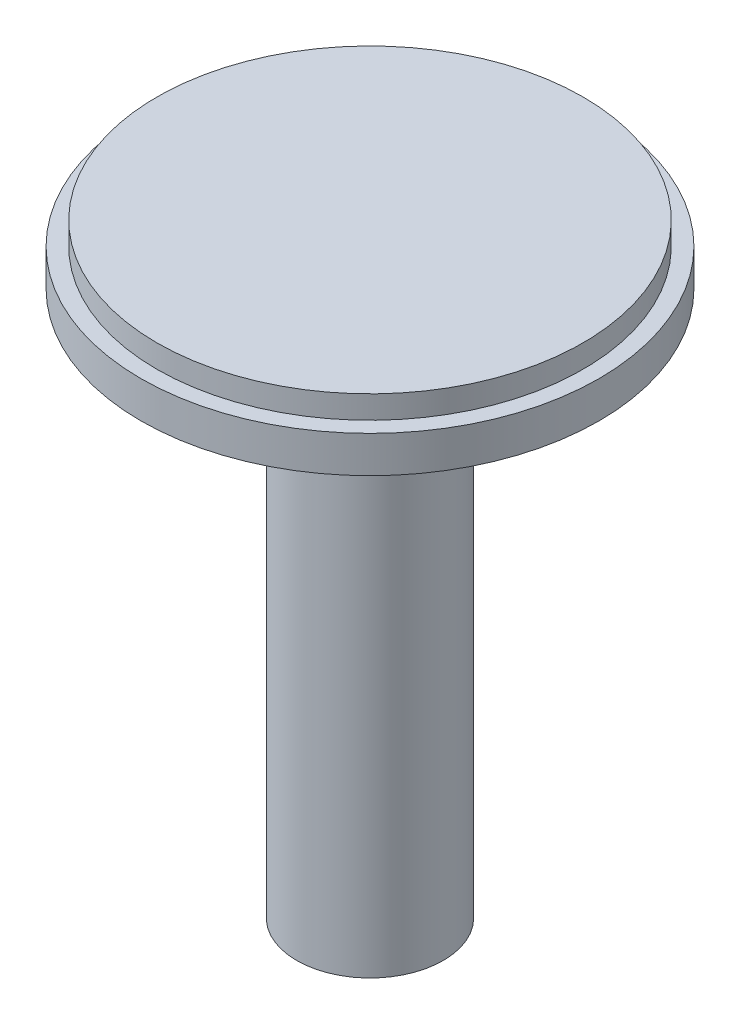
SolidWorks part; units mm, degrees
ref_plane "Front Plane" through (0, 0, 0) normal (0, 0, 1) x (1, 0, 0)
ref_plane "Top Plane" through (0, 0, 0) normal (0, 1, 0) x (1, 0, 0)
ref_plane "Right Plane" through (0, 0, 0) normal (1, 0, 0) x (0, 0, -1)
sketch "Sketch1" plane through (0, 0, 0) normal (0, 1, 0) x (1, 0, 0)
  circle A0 centre (0, 0) radius 16
extrude "Boss-Extrude1" add sketch "Sketch1" along normal blind 119
sketch "Sketch2" plane through (0, 119, 0) normal (0, 1, 0) x (1, 0, 0)
  circle A0 centre (0, 0) radius 50
extrude "Boss-Extrude2" add sketch "Sketch2" along normal blind 8
sketch "Sketch3" plane through (0, 127, 0) normal (0, 1, 0) x (1, 0, 0)
  circle A0 centre (0, 0) radius 46.5
extrude "Boss-Extrude3" add sketch "Sketch3" along normal blind 5
